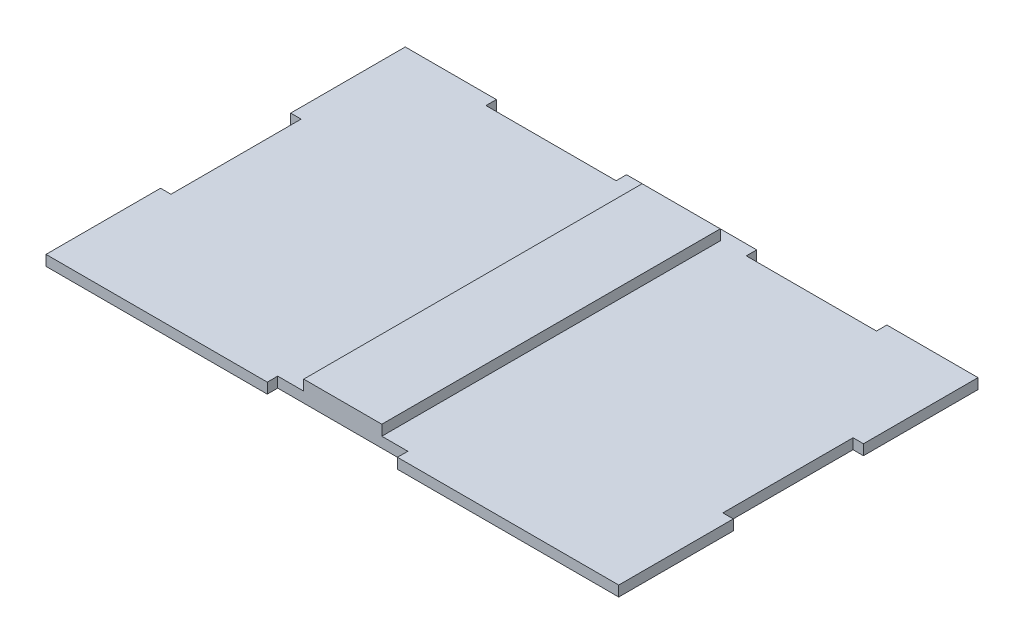
SolidWorks part; units mm, degrees
ref_plane "Front Plane" through (0, 0, 0) normal (0, 0, 1) x (1, 0, 0)
ref_plane "Top Plane" through (0, 0, 0) normal (0, 1, 0) x (1, 0, 0)
ref_plane "Right Plane" through (0, 0, 0) normal (1, 0, 0) x (0, 0, -1)
sketch "Sketch2" plane through (0, 0, 0) normal (0, 1, 0) x (1, 0, 0)
  line L0 (-110, 69) -> (-110, 25)
  line L1 (-110, -69) -> (-25, -69)
  line L2 (110, -69) -> (110, -25)
  line L3 (110, 69) -> (75, 69)
  line L4 (-106, 25) -> (-106, -25)
  line L5 (106, 25) -> (106, -25)
  line L6 (-106, 25) -> (-110, 25)
  line L7 (-106, -25) -> (-110, -25)
  line L8 (-110, -25) -> (-110, -69)
  line L9 (106, -25) -> (110, -25)
  line L10 (106, 25) -> (110, 25)
  line L11 (110, 25) -> (110, 69)
  line L12 (-75, 65) -> (-25, 65)
  line L13 (25, 65) -> (75, 65)
  line L14 (-75, 65) -> (-75, 69)
  line L15 (-25, 65) -> (-25, 69)
  line L16 (25, 65) -> (25, 69)
  line L17 (75, 65) -> (75, 69)
  line L18 (-75, 69) -> (-110, 69)
  line L19 (25, 69) -> (-25, 69)
  line L20 (-25, -65) -> (25, -65)
  line L21 (-25, -65) -> (-25, -69)
  line L22 (25, -65) -> (25, -69)
  line L23 (25, -69) -> (110, -69)
  point P5 (106, 0)
  point P11 (-106, 0)
  dimension "D1" = 220
  dimension "D2" = 138
  dimension "D3" = 50
  dimension "D4" = 50
  dimension "D5" = 4
  dimension "D6" = 4
  dimension "D7" = 69
  dimension "D8" = 50
  dimension "D9" = 50
  dimension "D10" = 50
  dimension "D11" = 35
  dimension "D12" = 4
  dimension "D13" = 110
  dimension "D14" = 50
  dimension "D15" = 4
  dimension "D16" = 85
extrude "Boss-Extrude1" add sketch "Sketch2" along normal blind 4
sketch "Sketch3" plane through (0, 4, 0) normal (0, 1, 0) x (1, 0, 0)
  line L0 (-15, -65) -> (-15, 65)
  line L1 (-25, -65) -> (25, -65) construction
  line L2 (-15, 65) -> (15, 65)
  line L3 (15, 65) -> (15, -65)
  line L4 (15, -65) -> (-15, -65)
  point P4 (0, -65)
  dimension "D1" = 130
  dimension "D2" = 30
extrude "Boss-Extrude2" add sketch "Sketch3" along normal blind 4
